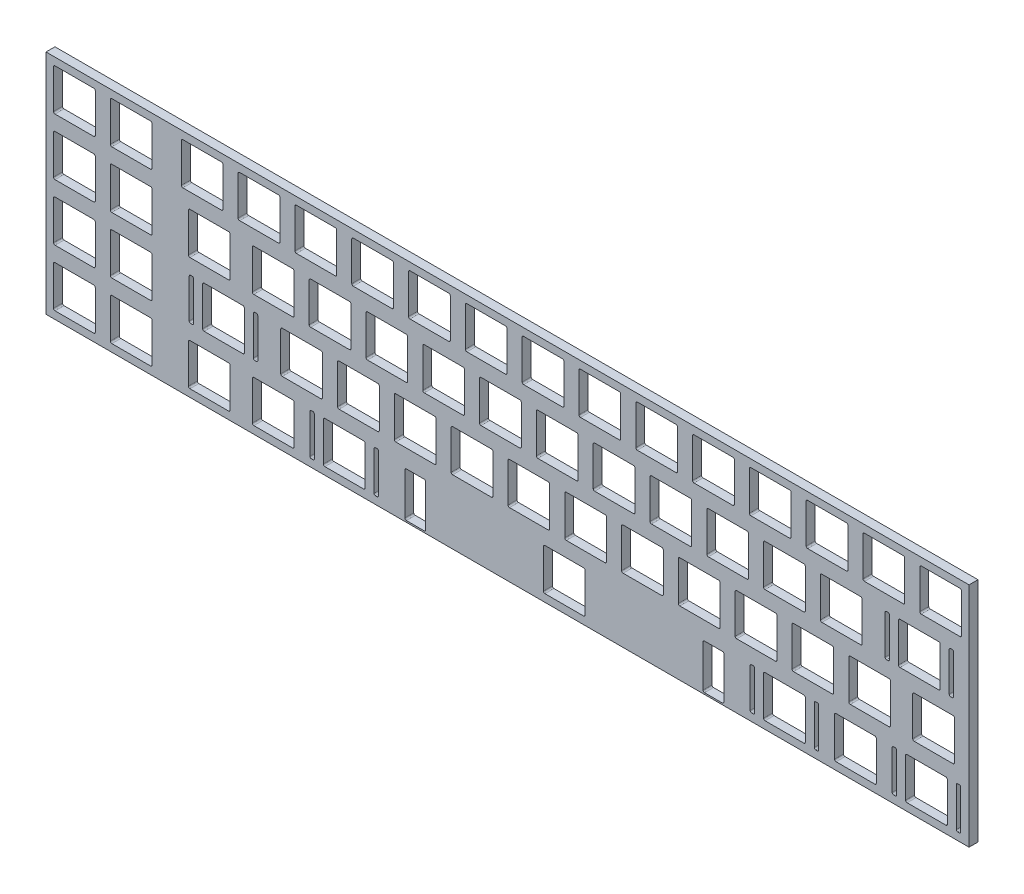
SolidWorks part; units mm, degrees
ref_plane "Front Plane" through (0, 0, 0) normal (0, 0, 1) x (1, 0, 0)
ref_plane "Top Plane" through (0, 0, 0) normal (0, 1, 0) x (1, 0, 0)
ref_plane "Right Plane" through (0, 0, 0) normal (1, 0, 0) x (0, 0, -1)
sketch "Model" plane through (0, 0, 0) normal (0, 0, 1) x (1, 0, 0)
  line L0 (3.025, -2.525) -> (16.025, -2.525)
  line L1 (3.025, -16.525) -> (16.025, -16.525)
  line L2 (2.525, -3.025) -> (2.525, -16.025)
  line L3 (16.525, -3.025) -> (16.525, -16.025)
  line L4 (22.075, -2.525) -> (35.075, -2.525)
  line L5 (22.075, -16.525) -> (35.075, -16.525)
  line L6 (21.575, -3.025) -> (21.575, -16.025)
  line L7 (35.575, -3.025) -> (35.575, -16.025)
  line L8 (45.8875, -2.525) -> (58.8875, -2.525)
  line L9 (45.8875, -16.525) -> (58.8875, -16.525)
  line L10 (45.3875, -3.025) -> (45.3875, -16.025)
  line L11 (59.3875, -3.025) -> (59.3875, -16.025)
  line L12 (64.9375, -2.525) -> (77.9375, -2.525)
  line L13 (64.9375, -16.525) -> (77.9375, -16.525)
  line L14 (64.4375, -3.025) -> (64.4375, -16.025)
  line L15 (78.4375, -3.025) -> (78.4375, -16.025)
  line L16 (83.9875, -2.525) -> (96.9875, -2.525)
  line L17 (83.9875, -16.525) -> (96.9875, -16.525)
  line L18 (83.4875, -3.025) -> (83.4875, -16.025)
  line L19 (97.4875, -3.025) -> (97.4875, -16.025)
  line L20 (103.0375, -2.525) -> (116.0375, -2.525)
  line L21 (103.0375, -16.525) -> (116.0375, -16.525)
  line L22 (102.5375, -3.025) -> (102.5375, -16.025)
  line L23 (116.5375, -3.025) -> (116.5375, -16.025)
  line L24 (122.0875, -2.525) -> (135.0875, -2.525)
  line L25 (122.0875, -16.525) -> (135.0875, -16.525)
  line L26 (121.5875, -3.025) -> (121.5875, -16.025)
  line L27 (135.5875, -3.025) -> (135.5875, -16.025)
  line L28 (141.1375, -2.525) -> (154.1375, -2.525)
  line L29 (141.1375, -16.525) -> (154.1375, -16.525)
  line L30 (140.6375, -3.025) -> (140.6375, -16.025)
  line L31 (154.6375, -3.025) -> (154.6375, -16.025)
  line L32 (160.1875, -2.525) -> (173.1875, -2.525)
  line L33 (160.1875, -16.525) -> (173.1875, -16.525)
  line L34 (159.6875, -3.025) -> (159.6875, -16.025)
  line L35 (173.6875, -3.025) -> (173.6875, -16.025)
  line L36 (179.2375, -2.525) -> (192.2375, -2.525)
  line L37 (179.2375, -16.525) -> (192.2375, -16.525)
  line L38 (178.7375, -3.025) -> (178.7375, -16.025)
  line L39 (192.7375, -3.025) -> (192.7375, -16.025)
  line L40 (198.2875, -2.525) -> (211.2875, -2.525)
  line L41 (198.2875, -16.525) -> (211.2875, -16.525)
  line L42 (197.7875, -3.025) -> (197.7875, -16.025)
  line L43 (211.7875, -3.025) -> (211.7875, -16.025)
  line L44 (217.3375, -2.525) -> (230.3375, -2.525)
  line L45 (217.3375, -16.525) -> (230.3375, -16.525)
  line L46 (216.8375, -3.025) -> (216.8375, -16.025)
  line L47 (230.8375, -3.025) -> (230.8375, -16.025)
  line L48 (236.3875, -2.525) -> (249.3875, -2.525)
  line L49 (236.3875, -16.525) -> (249.3875, -16.525)
  line L50 (235.8875, -3.025) -> (235.8875, -16.025)
  line L51 (249.8875, -3.025) -> (249.8875, -16.025)
  line L52 (255.4375, -2.525) -> (268.4375, -2.525)
  line L53 (255.4375, -16.525) -> (268.4375, -16.525)
  line L54 (254.9375, -3.025) -> (254.9375, -16.025)
  line L55 (268.9375, -3.025) -> (268.9375, -16.025)
  line L56 (274.4875, -2.525) -> (287.4875, -2.525)
  line L57 (274.4875, -16.525) -> (287.4875, -16.525)
  line L58 (273.9875, -3.025) -> (273.9875, -16.025)
  line L59 (287.9875, -3.025) -> (287.9875, -16.025)
  line L60 (293.5375, -2.525) -> (306.5375, -2.525)
  line L61 (293.5375, -16.525) -> (306.5375, -16.525)
  line L62 (293.0375, -3.025) -> (293.0375, -16.025)
  line L63 (307.0375, -3.025) -> (307.0375, -16.025)
  line L64 (3.025, -21.575) -> (16.025, -21.575)
  line L65 (3.025, -35.575) -> (16.025, -35.575)
  line L66 (2.525, -22.075) -> (2.525, -35.075)
  line L67 (16.525, -22.075) -> (16.525, -35.075)
  line L68 (22.075, -21.575) -> (35.075, -21.575)
  line L69 (22.075, -35.575) -> (35.075, -35.575)
  line L70 (21.575, -22.075) -> (21.575, -35.075)
  line L71 (35.575, -22.075) -> (35.575, -35.075)
  line L72 (48.2687, -21.575) -> (61.2687, -21.575)
  line L73 (48.2687, -35.575) -> (61.2687, -35.575)
  line L74 (47.7687, -22.075) -> (47.7687, -35.075)
  line L75 (61.7687, -22.075) -> (61.7687, -35.075)
  line L76 (69.7, -21.575) -> (82.7, -21.575)
  line L77 (69.7, -35.575) -> (82.7, -35.575)
  line L78 (69.2, -22.075) -> (69.2, -35.075)
  line L79 (83.2, -22.075) -> (83.2, -35.075)
  line L80 (88.75, -21.575) -> (101.75, -21.575)
  line L81 (88.75, -35.575) -> (101.75, -35.575)
  line L82 (88.25, -22.075) -> (88.25, -35.075)
  line L83 (102.25, -22.075) -> (102.25, -35.075)
  line L84 (107.8, -21.575) -> (120.8, -21.575)
  line L85 (107.8, -35.575) -> (120.8, -35.575)
  line L86 (107.3, -22.075) -> (107.3, -35.075)
  line L87 (121.3, -22.075) -> (121.3, -35.075)
  line L88 (126.85, -21.575) -> (139.85, -21.575)
  line L89 (126.85, -35.575) -> (139.85, -35.575)
  line L90 (126.35, -22.075) -> (126.35, -35.075)
  line L91 (140.35, -22.075) -> (140.35, -35.075)
  line L92 (145.9, -21.575) -> (158.9, -21.575)
  line L93 (145.9, -35.575) -> (158.9, -35.575)
  line L94 (145.4, -22.075) -> (145.4, -35.075)
  line L95 (159.4, -22.075) -> (159.4, -35.075)
  line L96 (164.95, -21.575) -> (177.95, -21.575)
  line L97 (164.95, -35.575) -> (177.95, -35.575)
  line L98 (164.45, -22.075) -> (164.45, -35.075)
  line L99 (178.45, -22.075) -> (178.45, -35.075)
  line L100 (184, -21.575) -> (197, -21.575)
  line L101 (184, -35.575) -> (197, -35.575)
  line L102 (183.5, -22.075) -> (183.5, -35.075)
  line L103 (197.5, -22.075) -> (197.5, -35.075)
  line L104 (203.05, -21.575) -> (216.05, -21.575)
  line L105 (203.05, -35.575) -> (216.05, -35.575)
  line L106 (202.55, -22.075) -> (202.55, -35.075)
  line L107 (216.55, -22.075) -> (216.55, -35.075)
  line L108 (222.1, -21.575) -> (235.1, -21.575)
  line L109 (222.1, -35.575) -> (235.1, -35.575)
  line L110 (221.6, -22.075) -> (221.6, -35.075)
  line L111 (235.6, -22.075) -> (235.6, -35.075)
  line L112 (241.15, -21.575) -> (254.15, -21.575)
  line L113 (241.15, -35.575) -> (254.15, -35.575)
  line L114 (240.65, -22.075) -> (240.65, -35.075)
  line L115 (254.65, -22.075) -> (254.65, -35.075)
  line L116 (260.2, -21.575) -> (273.2, -21.575)
  line L117 (260.2, -35.575) -> (273.2, -35.575)
  line L118 (259.7, -22.075) -> (259.7, -35.075)
  line L119 (273.7, -22.075) -> (273.7, -35.075)
  line L120 (286.3938, -21.575) -> (299.3938, -21.575)
  line L121 (286.3938, -35.575) -> (299.3938, -35.575)
  line L122 (285.8938, -22.075) -> (285.8938, -35.075)
  line L123 (299.8938, -22.075) -> (299.8938, -35.075)
  line L124 (281.8938, -21.575) -> (282.3938, -21.575)
  line L125 (281.8938, -35.575) -> (282.3938, -35.575)
  line L126 (281.3938, -22.075) -> (281.3938, -35.075)
  line L127 (282.8938, -22.075) -> (282.8938, -35.075)
  line L128 (303.3938, -21.575) -> (303.8938, -21.575)
  line L129 (303.3938, -35.575) -> (303.8938, -35.575)
  line L130 (302.8938, -22.075) -> (302.8938, -35.075)
  line L131 (304.3938, -22.075) -> (304.3938, -35.075)
  line L132 (3.025, -40.625) -> (16.025, -40.625)
  line L133 (3.025, -54.625) -> (16.025, -54.625)
  line L134 (2.525, -41.125) -> (2.525, -54.125)
  line L135 (16.525, -41.125) -> (16.525, -54.125)
  line L136 (22.075, -40.625) -> (35.075, -40.625)
  line L137 (22.075, -54.625) -> (35.075, -54.625)
  line L138 (21.575, -41.125) -> (21.575, -54.125)
  line L139 (35.575, -41.125) -> (35.575, -54.125)
  line L140 (53.0312, -40.625) -> (66.0312, -40.625)
  line L141 (53.0312, -54.625) -> (66.0312, -54.625)
  line L142 (52.5312, -41.125) -> (52.5312, -54.125)
  line L143 (66.5312, -41.125) -> (66.5312, -54.125)
  line L144 (48.5312, -40.625) -> (49.0312, -40.625)
  line L145 (48.5312, -54.625) -> (49.0312, -54.625)
  line L146 (48.0312, -41.125) -> (48.0312, -54.125)
  line L147 (49.5312, -41.125) -> (49.5312, -54.125)
  line L148 (70.0312, -40.625) -> (70.5312, -40.625)
  line L149 (70.0312, -54.625) -> (70.5312, -54.625)
  line L150 (69.5312, -41.125) -> (69.5312, -54.125)
  line L151 (71.0312, -41.125) -> (71.0312, -54.125)
  line L152 (79.225, -40.625) -> (92.225, -40.625)
  line L153 (79.225, -54.625) -> (92.225, -54.625)
  line L154 (78.725, -41.125) -> (78.725, -54.125)
  line L155 (92.725, -41.125) -> (92.725, -54.125)
  line L156 (98.275, -40.625) -> (111.275, -40.625)
  line L157 (98.275, -54.625) -> (111.275, -54.625)
  line L158 (97.775, -41.125) -> (97.775, -54.125)
  line L159 (111.775, -41.125) -> (111.775, -54.125)
  line L160 (117.325, -40.625) -> (130.325, -40.625)
  line L161 (117.325, -54.625) -> (130.325, -54.625)
  line L162 (116.825, -41.125) -> (116.825, -54.125)
  line L163 (130.825, -41.125) -> (130.825, -54.125)
  line L164 (136.375, -40.625) -> (149.375, -40.625)
  line L165 (136.375, -54.625) -> (149.375, -54.625)
  line L166 (135.875, -41.125) -> (135.875, -54.125)
  line L167 (149.875, -41.125) -> (149.875, -54.125)
  line L168 (155.425, -40.625) -> (168.425, -40.625)
  line L169 (155.425, -54.625) -> (168.425, -54.625)
  line L170 (154.925, -41.125) -> (154.925, -54.125)
  line L171 (168.925, -41.125) -> (168.925, -54.125)
  line L172 (174.475, -40.625) -> (187.475, -40.625)
  line L173 (174.475, -54.625) -> (187.475, -54.625)
  line L174 (173.975, -41.125) -> (173.975, -54.125)
  line L175 (187.975, -41.125) -> (187.975, -54.125)
  line L176 (193.525, -40.625) -> (206.525, -40.625)
  line L177 (193.525, -54.625) -> (206.525, -54.625)
  line L178 (193.025, -41.125) -> (193.025, -54.125)
  line L179 (207.025, -41.125) -> (207.025, -54.125)
  line L180 (212.575, -40.625) -> (225.575, -40.625)
  line L181 (212.575, -54.625) -> (225.575, -54.625)
  line L182 (212.075, -41.125) -> (212.075, -54.125)
  line L183 (226.075, -41.125) -> (226.075, -54.125)
  line L184 (231.625, -40.625) -> (244.625, -40.625)
  line L185 (231.625, -54.625) -> (244.625, -54.625)
  line L186 (231.125, -41.125) -> (231.125, -54.125)
  line L187 (245.125, -41.125) -> (245.125, -54.125)
  line L188 (250.675, -40.625) -> (263.675, -40.625)
  line L189 (250.675, -54.625) -> (263.675, -54.625)
  line L190 (250.175, -41.125) -> (250.175, -54.125)
  line L191 (264.175, -41.125) -> (264.175, -54.125)
  line L192 (269.725, -40.625) -> (282.725, -40.625)
  line L193 (269.725, -54.625) -> (282.725, -54.625)
  line L194 (269.225, -41.125) -> (269.225, -54.125)
  line L195 (283.225, -41.125) -> (283.225, -54.125)
  line L196 (291.1562, -40.625) -> (304.1562, -40.625)
  line L197 (291.1562, -54.625) -> (304.1562, -54.625)
  line L198 (290.6562, -41.125) -> (290.6562, -54.125)
  line L199 (304.6562, -41.125) -> (304.6562, -54.125)
  line L200 (3.025, -59.675) -> (16.025, -59.675)
  line L201 (3.025, -73.675) -> (16.025, -73.675)
  line L202 (2.525, -60.175) -> (2.525, -73.175)
  line L203 (16.525, -60.175) -> (16.525, -73.175)
  line L204 (22.075, -59.675) -> (35.075, -59.675)
  line L205 (22.075, -73.675) -> (35.075, -73.675)
  line L206 (21.575, -60.175) -> (21.575, -73.175)
  line L207 (35.575, -60.175) -> (35.575, -73.175)
  line L208 (48.2687, -59.675) -> (61.2687, -59.675)
  line L209 (48.2687, -73.675) -> (61.2687, -73.675)
  line L210 (47.7687, -60.175) -> (47.7687, -73.175)
  line L211 (61.7687, -60.175) -> (61.7687, -73.175)
  line L212 (69.7, -59.675) -> (82.7, -59.675)
  line L213 (69.7, -73.675) -> (82.7, -73.675)
  line L214 (69.2, -60.175) -> (69.2, -73.175)
  line L215 (83.2, -60.175) -> (83.2, -73.175)
  line L216 (93.5125, -59.675) -> (106.5125, -59.675)
  line L217 (93.5125, -73.675) -> (106.5125, -73.675)
  line L218 (93.0125, -60.175) -> (93.0125, -73.175)
  line L219 (107.0125, -60.175) -> (107.0125, -73.175)
  line L220 (89.0125, -59.675) -> (89.5125, -59.675)
  line L221 (89.0125, -73.675) -> (89.5125, -73.675)
  line L222 (88.5125, -60.175) -> (88.5125, -73.175)
  line L223 (90.0125, -60.175) -> (90.0125, -73.175)
  line L224 (110.5125, -59.675) -> (111.0125, -59.675)
  line L225 (110.5125, -73.675) -> (111.0125, -73.675)
  line L226 (110.0125, -60.175) -> (110.0125, -73.175)
  line L227 (111.5125, -60.175) -> (111.5125, -73.175)
  line L228 (167.3313, -59.675) -> (180.3313, -59.675)
  line L229 (167.3313, -73.675) -> (180.3313, -73.675)
  line L230 (166.8313, -60.175) -> (166.8313, -73.175)
  line L231 (180.8313, -60.175) -> (180.8313, -73.175)
  line L232 (120.8312, -60.675) -> (126.8313, -60.675)
  line L233 (120.8312, -75.675) -> (126.8313, -75.675)
  line L234 (120.3312, -61.175) -> (120.3312, -75.175)
  line L235 (127.3313, -61.175) -> (127.3313, -75.175)
  line L236 (220.8313, -60.675) -> (226.8313, -60.675)
  line L237 (220.8313, -75.675) -> (226.8313, -75.675)
  line L238 (220.3313, -61.175) -> (220.3313, -75.175)
  line L239 (227.3313, -61.175) -> (227.3313, -75.175)
  line L240 (241.15, -59.675) -> (254.15, -59.675)
  line L241 (241.15, -73.675) -> (254.15, -73.675)
  line L242 (240.65, -60.175) -> (240.65, -73.175)
  line L243 (254.65, -60.175) -> (254.65, -73.175)
  line L244 (236.65, -59.675) -> (237.15, -59.675)
  line L245 (236.65, -73.675) -> (237.15, -73.675)
  line L246 (236.15, -60.175) -> (236.15, -73.175)
  line L247 (237.65, -60.175) -> (237.65, -73.175)
  line L248 (258.15, -59.675) -> (258.65, -59.675)
  line L249 (258.15, -73.675) -> (258.65, -73.675)
  line L250 (257.65, -60.175) -> (257.65, -73.175)
  line L251 (259.15, -60.175) -> (259.15, -73.175)
  line L252 (264.9625, -59.675) -> (277.9625, -59.675)
  line L253 (264.9625, -73.675) -> (277.9625, -73.675)
  line L254 (264.4625, -60.175) -> (264.4625, -73.175)
  line L255 (278.4625, -60.175) -> (278.4625, -73.175)
  line L256 (288.775, -59.675) -> (301.775, -59.675)
  line L257 (288.775, -73.675) -> (301.775, -73.675)
  line L258 (288.275, -60.175) -> (288.275, -73.175)
  line L259 (302.275, -60.175) -> (302.275, -73.175)
  line L260 (284.275, -59.675) -> (284.775, -59.675)
  line L261 (284.275, -73.675) -> (284.775, -73.675)
  line L262 (283.775, -60.175) -> (283.775, -73.175)
  line L263 (285.275, -60.175) -> (285.275, -73.175)
  line L264 (305.775, -59.675) -> (306.275, -59.675)
  line L265 (305.775, -73.675) -> (306.275, -73.675)
  line L266 (305.275, -60.175) -> (305.275, -73.175)
  line L267 (306.775, -60.175) -> (306.775, -73.175)
  line L268 (0, -76.2) -> (309.5625, -76.2)
  line L269 (0, 0) -> (309.5625, 0)
  line L270 (0, -76.2) -> (0, 0)
  line L271 (309.5625, -76.2) -> (309.5625, 0)
  arc A0 (3.025, -2.525) -> (2.525, -3.025) centre (3.025, -3.025) ccw
  arc A1 (16.525, -3.025) -> (16.025, -2.525) centre (16.025, -3.025) ccw
  arc A2 (2.525, -16.025) -> (3.025, -16.525) centre (3.025, -16.025) ccw
  arc A3 (16.025, -16.525) -> (16.525, -16.025) centre (16.025, -16.025) ccw
  arc A4 (22.075, -2.525) -> (21.575, -3.025) centre (22.075, -3.025) ccw
  arc A5 (35.575, -3.025) -> (35.075, -2.525) centre (35.075, -3.025) ccw
  arc A6 (21.575, -16.025) -> (22.075, -16.525) centre (22.075, -16.025) ccw
  arc A7 (35.075, -16.525) -> (35.575, -16.025) centre (35.075, -16.025) ccw
  arc A8 (45.8875, -2.525) -> (45.3875, -3.025) centre (45.8875, -3.025) ccw
  arc A9 (59.3875, -3.025) -> (58.8875, -2.525) centre (58.8875, -3.025) ccw
  arc A10 (45.3875, -16.025) -> (45.8875, -16.525) centre (45.8875, -16.025) ccw
  arc A11 (58.8875, -16.525) -> (59.3875, -16.025) centre (58.8875, -16.025) ccw
  arc A12 (64.9375, -2.525) -> (64.4375, -3.025) centre (64.9375, -3.025) ccw
  arc A13 (78.4375, -3.025) -> (77.9375, -2.525) centre (77.9375, -3.025) ccw
  arc A14 (64.4375, -16.025) -> (64.9375, -16.525) centre (64.9375, -16.025) ccw
  arc A15 (77.9375, -16.525) -> (78.4375, -16.025) centre (77.9375, -16.025) ccw
  arc A16 (83.9875, -2.525) -> (83.4875, -3.025) centre (83.9875, -3.025) ccw
  arc A17 (97.4875, -3.025) -> (96.9875, -2.525) centre (96.9875, -3.025) ccw
  arc A18 (83.4875, -16.025) -> (83.9875, -16.525) centre (83.9875, -16.025) ccw
  arc A19 (96.9875, -16.525) -> (97.4875, -16.025) centre (96.9875, -16.025) ccw
  arc A20 (103.0375, -2.525) -> (102.5375, -3.025) centre (103.0375, -3.025) ccw
  arc A21 (116.5375, -3.025) -> (116.0375, -2.525) centre (116.0375, -3.025) ccw
  arc A22 (102.5375, -16.025) -> (103.0375, -16.525) centre (103.0375, -16.025) ccw
  arc A23 (116.0375, -16.525) -> (116.5375, -16.025) centre (116.0375, -16.025) ccw
  arc A24 (122.0875, -2.525) -> (121.5875, -3.025) centre (122.0875, -3.025) ccw
  arc A25 (135.5875, -3.025) -> (135.0875, -2.525) centre (135.0875, -3.025) ccw
  arc A26 (121.5875, -16.025) -> (122.0875, -16.525) centre (122.0875, -16.025) ccw
  arc A27 (135.0875, -16.525) -> (135.5875, -16.025) centre (135.0875, -16.025) ccw
  arc A28 (141.1375, -2.525) -> (140.6375, -3.025) centre (141.1375, -3.025) ccw
  arc A29 (154.6375, -3.025) -> (154.1375, -2.525) centre (154.1375, -3.025) ccw
  arc A30 (140.6375, -16.025) -> (141.1375, -16.525) centre (141.1375, -16.025) ccw
  arc A31 (154.1375, -16.525) -> (154.6375, -16.025) centre (154.1375, -16.025) ccw
  arc A32 (160.1875, -2.525) -> (159.6875, -3.025) centre (160.1875, -3.025) ccw
  arc A33 (173.6875, -3.025) -> (173.1875, -2.525) centre (173.1875, -3.025) ccw
  arc A34 (159.6875, -16.025) -> (160.1875, -16.525) centre (160.1875, -16.025) ccw
  arc A35 (173.1875, -16.525) -> (173.6875, -16.025) centre (173.1875, -16.025) ccw
  arc A36 (179.2375, -2.525) -> (178.7375, -3.025) centre (179.2375, -3.025) ccw
  arc A37 (192.7375, -3.025) -> (192.2375, -2.525) centre (192.2375, -3.025) ccw
  arc A38 (178.7375, -16.025) -> (179.2375, -16.525) centre (179.2375, -16.025) ccw
  arc A39 (192.2375, -16.525) -> (192.7375, -16.025) centre (192.2375, -16.025) ccw
  arc A40 (198.2875, -2.525) -> (197.7875, -3.025) centre (198.2875, -3.025) ccw
  arc A41 (211.7875, -3.025) -> (211.2875, -2.525) centre (211.2875, -3.025) ccw
  arc A42 (197.7875, -16.025) -> (198.2875, -16.525) centre (198.2875, -16.025) ccw
  arc A43 (211.2875, -16.525) -> (211.7875, -16.025) centre (211.2875, -16.025) ccw
  arc A44 (217.3375, -2.525) -> (216.8375, -3.025) centre (217.3375, -3.025) ccw
  arc A45 (230.8375, -3.025) -> (230.3375, -2.525) centre (230.3375, -3.025) ccw
  arc A46 (216.8375, -16.025) -> (217.3375, -16.525) centre (217.3375, -16.025) ccw
  arc A47 (230.3375, -16.525) -> (230.8375, -16.025) centre (230.3375, -16.025) ccw
  arc A48 (236.3875, -2.525) -> (235.8875, -3.025) centre (236.3875, -3.025) ccw
  arc A49 (249.8875, -3.025) -> (249.3875, -2.525) centre (249.3875, -3.025) ccw
  arc A50 (235.8875, -16.025) -> (236.3875, -16.525) centre (236.3875, -16.025) ccw
  arc A51 (249.3875, -16.525) -> (249.8875, -16.025) centre (249.3875, -16.025) ccw
  arc A52 (255.4375, -2.525) -> (254.9375, -3.025) centre (255.4375, -3.025) ccw
  arc A53 (268.9375, -3.025) -> (268.4375, -2.525) centre (268.4375, -3.025) ccw
  arc A54 (254.9375, -16.025) -> (255.4375, -16.525) centre (255.4375, -16.025) ccw
  arc A55 (268.4375, -16.525) -> (268.9375, -16.025) centre (268.4375, -16.025) ccw
  arc A56 (274.4875, -2.525) -> (273.9875, -3.025) centre (274.4875, -3.025) ccw
  arc A57 (287.9875, -3.025) -> (287.4875, -2.525) centre (287.4875, -3.025) ccw
  arc A58 (273.9875, -16.025) -> (274.4875, -16.525) centre (274.4875, -16.025) ccw
  arc A59 (287.4875, -16.525) -> (287.9875, -16.025) centre (287.4875, -16.025) ccw
  arc A60 (293.5375, -2.525) -> (293.0375, -3.025) centre (293.5375, -3.025) ccw
  arc A61 (307.0375, -3.025) -> (306.5375, -2.525) centre (306.5375, -3.025) ccw
  arc A62 (293.0375, -16.025) -> (293.5375, -16.525) centre (293.5375, -16.025) ccw
  arc A63 (306.5375, -16.525) -> (307.0375, -16.025) centre (306.5375, -16.025) ccw
  arc A64 (3.025, -21.575) -> (2.525, -22.075) centre (3.025, -22.075) ccw
  arc A65 (16.525, -22.075) -> (16.025, -21.575) centre (16.025, -22.075) ccw
  arc A66 (2.525, -35.075) -> (3.025, -35.575) centre (3.025, -35.075) ccw
  arc A67 (16.025, -35.575) -> (16.525, -35.075) centre (16.025, -35.075) ccw
  arc A68 (22.075, -21.575) -> (21.575, -22.075) centre (22.075, -22.075) ccw
  arc A69 (35.575, -22.075) -> (35.075, -21.575) centre (35.075, -22.075) ccw
  arc A70 (21.575, -35.075) -> (22.075, -35.575) centre (22.075, -35.075) ccw
  arc A71 (35.075, -35.575) -> (35.575, -35.075) centre (35.075, -35.075) ccw
  arc A72 (48.2687, -21.575) -> (47.7687, -22.075) centre (48.2687, -22.075) ccw
  arc A73 (61.7687, -22.075) -> (61.2687, -21.575) centre (61.2687, -22.075) ccw
  arc A74 (47.7687, -35.075) -> (48.2687, -35.575) centre (48.2687, -35.075) ccw
  arc A75 (61.2687, -35.575) -> (61.7687, -35.075) centre (61.2687, -35.075) ccw
  arc A76 (69.7, -21.575) -> (69.2, -22.075) centre (69.7, -22.075) ccw
  arc A77 (83.2, -22.075) -> (82.7, -21.575) centre (82.7, -22.075) ccw
  arc A78 (69.2, -35.075) -> (69.7, -35.575) centre (69.7, -35.075) ccw
  arc A79 (82.7, -35.575) -> (83.2, -35.075) centre (82.7, -35.075) ccw
  arc A80 (88.75, -21.575) -> (88.25, -22.075) centre (88.75, -22.075) ccw
  arc A81 (102.25, -22.075) -> (101.75, -21.575) centre (101.75, -22.075) ccw
  arc A82 (88.25, -35.075) -> (88.75, -35.575) centre (88.75, -35.075) ccw
  arc A83 (101.75, -35.575) -> (102.25, -35.075) centre (101.75, -35.075) ccw
  arc A84 (107.8, -21.575) -> (107.3, -22.075) centre (107.8, -22.075) ccw
  arc A85 (121.3, -22.075) -> (120.8, -21.575) centre (120.8, -22.075) ccw
  arc A86 (107.3, -35.075) -> (107.8, -35.575) centre (107.8, -35.075) ccw
  arc A87 (120.8, -35.575) -> (121.3, -35.075) centre (120.8, -35.075) ccw
  arc A88 (126.85, -21.575) -> (126.35, -22.075) centre (126.85, -22.075) ccw
  arc A89 (140.35, -22.075) -> (139.85, -21.575) centre (139.85, -22.075) ccw
  arc A90 (126.35, -35.075) -> (126.85, -35.575) centre (126.85, -35.075) ccw
  arc A91 (139.85, -35.575) -> (140.35, -35.075) centre (139.85, -35.075) ccw
  arc A92 (145.9, -21.575) -> (145.4, -22.075) centre (145.9, -22.075) ccw
  arc A93 (159.4, -22.075) -> (158.9, -21.575) centre (158.9, -22.075) ccw
  arc A94 (145.4, -35.075) -> (145.9, -35.575) centre (145.9, -35.075) ccw
  arc A95 (158.9, -35.575) -> (159.4, -35.075) centre (158.9, -35.075) ccw
  arc A96 (164.95, -21.575) -> (164.45, -22.075) centre (164.95, -22.075) ccw
  arc A97 (178.45, -22.075) -> (177.95, -21.575) centre (177.95, -22.075) ccw
  arc A98 (164.45, -35.075) -> (164.95, -35.575) centre (164.95, -35.075) ccw
  arc A99 (177.95, -35.575) -> (178.45, -35.075) centre (177.95, -35.075) ccw
  arc A100 (184, -21.575) -> (183.5, -22.075) centre (184, -22.075) ccw
  arc A101 (197.5, -22.075) -> (197, -21.575) centre (197, -22.075) ccw
  arc A102 (183.5, -35.075) -> (184, -35.575) centre (184, -35.075) ccw
  arc A103 (197, -35.575) -> (197.5, -35.075) centre (197, -35.075) ccw
  arc A104 (203.05, -21.575) -> (202.55, -22.075) centre (203.05, -22.075) ccw
  arc A105 (216.55, -22.075) -> (216.05, -21.575) centre (216.05, -22.075) ccw
  arc A106 (202.55, -35.075) -> (203.05, -35.575) centre (203.05, -35.075) ccw
  arc A107 (216.05, -35.575) -> (216.55, -35.075) centre (216.05, -35.075) ccw
  arc A108 (222.1, -21.575) -> (221.6, -22.075) centre (222.1, -22.075) ccw
  arc A109 (235.6, -22.075) -> (235.1, -21.575) centre (235.1, -22.075) ccw
  arc A110 (221.6, -35.075) -> (222.1, -35.575) centre (222.1, -35.075) ccw
  arc A111 (235.1, -35.575) -> (235.6, -35.075) centre (235.1, -35.075) ccw
  arc A112 (241.15, -21.575) -> (240.65, -22.075) centre (241.15, -22.075) ccw
  arc A113 (254.65, -22.075) -> (254.15, -21.575) centre (254.15, -22.075) ccw
  arc A114 (240.65, -35.075) -> (241.15, -35.575) centre (241.15, -35.075) ccw
  arc A115 (254.15, -35.575) -> (254.65, -35.075) centre (254.15, -35.075) ccw
  arc A116 (260.2, -21.575) -> (259.7, -22.075) centre (260.2, -22.075) ccw
  arc A117 (273.7, -22.075) -> (273.2, -21.575) centre (273.2, -22.075) ccw
  arc A118 (259.7, -35.075) -> (260.2, -35.575) centre (260.2, -35.075) ccw
  arc A119 (273.2, -35.575) -> (273.7, -35.075) centre (273.2, -35.075) ccw
  arc A120 (286.3938, -21.575) -> (285.8938, -22.075) centre (286.3938, -22.075) ccw
  arc A121 (299.8938, -22.075) -> (299.3938, -21.575) centre (299.3938, -22.075) ccw
  arc A122 (285.8938, -35.075) -> (286.3938, -35.575) centre (286.3938, -35.075) ccw
  arc A123 (299.3938, -35.575) -> (299.8938, -35.075) centre (299.3938, -35.075) ccw
  arc A124 (281.8938, -21.575) -> (281.3938, -22.075) centre (281.8938, -22.075) ccw
  arc A125 (282.8938, -22.075) -> (282.3938, -21.575) centre (282.3938, -22.075) ccw
  arc A126 (281.3938, -35.075) -> (281.8938, -35.575) centre (281.8938, -35.075) ccw
  arc A127 (282.3938, -35.575) -> (282.8938, -35.075) centre (282.3938, -35.075) ccw
  arc A128 (303.3938, -21.575) -> (302.8938, -22.075) centre (303.3938, -22.075) ccw
  arc A129 (304.3938, -22.075) -> (303.8938, -21.575) centre (303.8938, -22.075) ccw
  arc A130 (302.8938, -35.075) -> (303.3938, -35.575) centre (303.3938, -35.075) ccw
  arc A131 (303.8938, -35.575) -> (304.3938, -35.075) centre (303.8938, -35.075) ccw
  arc A132 (3.025, -40.625) -> (2.525, -41.125) centre (3.025, -41.125) ccw
  arc A133 (16.525, -41.125) -> (16.025, -40.625) centre (16.025, -41.125) ccw
  arc A134 (2.525, -54.125) -> (3.025, -54.625) centre (3.025, -54.125) ccw
  arc A135 (16.025, -54.625) -> (16.525, -54.125) centre (16.025, -54.125) ccw
  arc A136 (22.075, -40.625) -> (21.575, -41.125) centre (22.075, -41.125) ccw
  arc A137 (35.575, -41.125) -> (35.075, -40.625) centre (35.075, -41.125) ccw
  arc A138 (21.575, -54.125) -> (22.075, -54.625) centre (22.075, -54.125) ccw
  arc A139 (35.075, -54.625) -> (35.575, -54.125) centre (35.075, -54.125) ccw
  arc A140 (53.0312, -40.625) -> (52.5312, -41.125) centre (53.0312, -41.125) ccw
  arc A141 (66.5312, -41.125) -> (66.0312, -40.625) centre (66.0312, -41.125) ccw
  arc A142 (52.5312, -54.125) -> (53.0312, -54.625) centre (53.0312, -54.125) ccw
  arc A143 (66.0312, -54.625) -> (66.5312, -54.125) centre (66.0312, -54.125) ccw
  arc A144 (48.5312, -40.625) -> (48.0312, -41.125) centre (48.5312, -41.125) ccw
  arc A145 (49.5312, -41.125) -> (49.0312, -40.625) centre (49.0312, -41.125) ccw
  arc A146 (48.0312, -54.125) -> (48.5312, -54.625) centre (48.5312, -54.125) ccw
  arc A147 (49.0312, -54.625) -> (49.5312, -54.125) centre (49.0312, -54.125) ccw
  arc A148 (70.0312, -40.625) -> (69.5312, -41.125) centre (70.0312, -41.125) ccw
  arc A149 (71.0312, -41.125) -> (70.5312, -40.625) centre (70.5312, -41.125) ccw
  arc A150 (69.5312, -54.125) -> (70.0312, -54.625) centre (70.0312, -54.125) ccw
  arc A151 (70.5312, -54.625) -> (71.0312, -54.125) centre (70.5312, -54.125) ccw
  arc A152 (79.225, -40.625) -> (78.725, -41.125) centre (79.225, -41.125) ccw
  arc A153 (92.725, -41.125) -> (92.225, -40.625) centre (92.225, -41.125) ccw
  arc A154 (78.725, -54.125) -> (79.225, -54.625) centre (79.225, -54.125) ccw
  arc A155 (92.225, -54.625) -> (92.725, -54.125) centre (92.225, -54.125) ccw
  arc A156 (98.275, -40.625) -> (97.775, -41.125) centre (98.275, -41.125) ccw
  arc A157 (111.775, -41.125) -> (111.275, -40.625) centre (111.275, -41.125) ccw
  arc A158 (97.775, -54.125) -> (98.275, -54.625) centre (98.275, -54.125) ccw
  arc A159 (111.275, -54.625) -> (111.775, -54.125) centre (111.275, -54.125) ccw
  arc A160 (117.325, -40.625) -> (116.825, -41.125) centre (117.325, -41.125) ccw
  arc A161 (130.825, -41.125) -> (130.325, -40.625) centre (130.325, -41.125) ccw
  arc A162 (116.825, -54.125) -> (117.325, -54.625) centre (117.325, -54.125) ccw
  arc A163 (130.325, -54.625) -> (130.825, -54.125) centre (130.325, -54.125) ccw
  arc A164 (136.375, -40.625) -> (135.875, -41.125) centre (136.375, -41.125) ccw
  arc A165 (149.875, -41.125) -> (149.375, -40.625) centre (149.375, -41.125) ccw
  arc A166 (135.875, -54.125) -> (136.375, -54.625) centre (136.375, -54.125) ccw
  arc A167 (149.375, -54.625) -> (149.875, -54.125) centre (149.375, -54.125) ccw
  arc A168 (155.425, -40.625) -> (154.925, -41.125) centre (155.425, -41.125) ccw
  arc A169 (168.925, -41.125) -> (168.425, -40.625) centre (168.425, -41.125) ccw
  arc A170 (154.925, -54.125) -> (155.425, -54.625) centre (155.425, -54.125) ccw
  arc A171 (168.425, -54.625) -> (168.925, -54.125) centre (168.425, -54.125) ccw
  arc A172 (174.475, -40.625) -> (173.975, -41.125) centre (174.475, -41.125) ccw
  arc A173 (187.975, -41.125) -> (187.475, -40.625) centre (187.475, -41.125) ccw
  arc A174 (173.975, -54.125) -> (174.475, -54.625) centre (174.475, -54.125) ccw
  arc A175 (187.475, -54.625) -> (187.975, -54.125) centre (187.475, -54.125) ccw
  arc A176 (193.525, -40.625) -> (193.025, -41.125) centre (193.525, -41.125) ccw
  arc A177 (207.025, -41.125) -> (206.525, -40.625) centre (206.525, -41.125) ccw
  arc A178 (193.025, -54.125) -> (193.525, -54.625) centre (193.525, -54.125) ccw
  arc A179 (206.525, -54.625) -> (207.025, -54.125) centre (206.525, -54.125) ccw
  arc A180 (212.575, -40.625) -> (212.075, -41.125) centre (212.575, -41.125) ccw
  arc A181 (226.075, -41.125) -> (225.575, -40.625) centre (225.575, -41.125) ccw
  arc A182 (212.075, -54.125) -> (212.575, -54.625) centre (212.575, -54.125) ccw
  arc A183 (225.575, -54.625) -> (226.075, -54.125) centre (225.575, -54.125) ccw
  arc A184 (231.625, -40.625) -> (231.125, -41.125) centre (231.625, -41.125) ccw
  arc A185 (245.125, -41.125) -> (244.625, -40.625) centre (244.625, -41.125) ccw
  arc A186 (231.125, -54.125) -> (231.625, -54.625) centre (231.625, -54.125) ccw
  arc A187 (244.625, -54.625) -> (245.125, -54.125) centre (244.625, -54.125) ccw
  arc A188 (250.675, -40.625) -> (250.175, -41.125) centre (250.675, -41.125) ccw
  arc A189 (264.175, -41.125) -> (263.675, -40.625) centre (263.675, -41.125) ccw
  arc A190 (250.175, -54.125) -> (250.675, -54.625) centre (250.675, -54.125) ccw
  arc A191 (263.675, -54.625) -> (264.175, -54.125) centre (263.675, -54.125) ccw
  arc A192 (269.725, -40.625) -> (269.225, -41.125) centre (269.725, -41.125) ccw
  arc A193 (283.225, -41.125) -> (282.725, -40.625) centre (282.725, -41.125) ccw
  arc A194 (269.225, -54.125) -> (269.725, -54.625) centre (269.725, -54.125) ccw
  arc A195 (282.725, -54.625) -> (283.225, -54.125) centre (282.725, -54.125) ccw
  arc A196 (291.1562, -40.625) -> (290.6562, -41.125) centre (291.1562, -41.125) ccw
  arc A197 (304.6562, -41.125) -> (304.1562, -40.625) centre (304.1562, -41.125) ccw
  arc A198 (290.6562, -54.125) -> (291.1562, -54.625) centre (291.1562, -54.125) ccw
  arc A199 (304.1562, -54.625) -> (304.6562, -54.125) centre (304.1562, -54.125) ccw
  arc A200 (3.025, -59.675) -> (2.525, -60.175) centre (3.025, -60.175) ccw
  arc A201 (16.525, -60.175) -> (16.025, -59.675) centre (16.025, -60.175) ccw
  arc A202 (2.525, -73.175) -> (3.025, -73.675) centre (3.025, -73.175) ccw
  arc A203 (16.025, -73.675) -> (16.525, -73.175) centre (16.025, -73.175) ccw
  arc A204 (22.075, -59.675) -> (21.575, -60.175) centre (22.075, -60.175) ccw
  arc A205 (35.575, -60.175) -> (35.075, -59.675) centre (35.075, -60.175) ccw
  arc A206 (21.575, -73.175) -> (22.075, -73.675) centre (22.075, -73.175) ccw
  arc A207 (35.075, -73.675) -> (35.575, -73.175) centre (35.075, -73.175) ccw
  arc A208 (48.2687, -59.675) -> (47.7687, -60.175) centre (48.2687, -60.175) ccw
  arc A209 (61.7687, -60.175) -> (61.2687, -59.675) centre (61.2687, -60.175) ccw
  arc A210 (47.7687, -73.175) -> (48.2687, -73.675) centre (48.2687, -73.175) ccw
  arc A211 (61.2687, -73.675) -> (61.7687, -73.175) centre (61.2687, -73.175) ccw
  arc A212 (69.7, -59.675) -> (69.2, -60.175) centre (69.7, -60.175) ccw
  arc A213 (83.2, -60.175) -> (82.7, -59.675) centre (82.7, -60.175) ccw
  arc A214 (69.2, -73.175) -> (69.7, -73.675) centre (69.7, -73.175) ccw
  arc A215 (82.7, -73.675) -> (83.2, -73.175) centre (82.7, -73.175) ccw
  arc A216 (93.5125, -59.675) -> (93.0125, -60.175) centre (93.5125, -60.175) ccw
  arc A217 (107.0125, -60.175) -> (106.5125, -59.675) centre (106.5125, -60.175) ccw
  arc A218 (93.0125, -73.175) -> (93.5125, -73.675) centre (93.5125, -73.175) ccw
  arc A219 (106.5125, -73.675) -> (107.0125, -73.175) centre (106.5125, -73.175) ccw
  arc A220 (89.0125, -59.675) -> (88.5125, -60.175) centre (89.0125, -60.175) ccw
  arc A221 (90.0125, -60.175) -> (89.5125, -59.675) centre (89.5125, -60.175) ccw
  arc A222 (88.5125, -73.175) -> (89.0125, -73.675) centre (89.0125, -73.175) ccw
  arc A223 (89.5125, -73.675) -> (90.0125, -73.175) centre (89.5125, -73.175) ccw
  arc A224 (110.5125, -59.675) -> (110.0125, -60.175) centre (110.5125, -60.175) ccw
  arc A225 (111.5125, -60.175) -> (111.0125, -59.675) centre (111.0125, -60.175) ccw
  arc A226 (110.0125, -73.175) -> (110.5125, -73.675) centre (110.5125, -73.175) ccw
  arc A227 (111.0125, -73.675) -> (111.5125, -73.175) centre (111.0125, -73.175) ccw
  arc A228 (167.3313, -59.675) -> (166.8313, -60.175) centre (167.3313, -60.175) ccw
  arc A229 (180.8313, -60.175) -> (180.3313, -59.675) centre (180.3313, -60.175) ccw
  arc A230 (166.8313, -73.175) -> (167.3313, -73.675) centre (167.3313, -73.175) ccw
  arc A231 (180.3313, -73.675) -> (180.8313, -73.175) centre (180.3313, -73.175) ccw
  arc A232 (120.8312, -60.675) -> (120.3312, -61.175) centre (120.8312, -61.175) ccw
  arc A233 (127.3313, -61.175) -> (126.8313, -60.675) centre (126.8313, -61.175) ccw
  arc A234 (120.3312, -75.175) -> (120.8312, -75.675) centre (120.8312, -75.175) ccw
  arc A235 (126.8313, -75.675) -> (127.3313, -75.175) centre (126.8313, -75.175) ccw
  arc A236 (220.8313, -60.675) -> (220.3313, -61.175) centre (220.8313, -61.175) ccw
  arc A237 (227.3313, -61.175) -> (226.8313, -60.675) centre (226.8313, -61.175) ccw
  arc A238 (220.3313, -75.175) -> (220.8313, -75.675) centre (220.8313, -75.175) ccw
  arc A239 (226.8313, -75.675) -> (227.3313, -75.175) centre (226.8313, -75.175) ccw
  arc A240 (241.15, -59.675) -> (240.65, -60.175) centre (241.15, -60.175) ccw
  arc A241 (254.65, -60.175) -> (254.15, -59.675) centre (254.15, -60.175) ccw
  arc A242 (240.65, -73.175) -> (241.15, -73.675) centre (241.15, -73.175) ccw
  arc A243 (254.15, -73.675) -> (254.65, -73.175) centre (254.15, -73.175) ccw
  arc A244 (236.65, -59.675) -> (236.15, -60.175) centre (236.65, -60.175) ccw
  arc A245 (237.65, -60.175) -> (237.15, -59.675) centre (237.15, -60.175) ccw
  arc A246 (236.15, -73.175) -> (236.65, -73.675) centre (236.65, -73.175) ccw
  arc A247 (237.15, -73.675) -> (237.65, -73.175) centre (237.15, -73.175) ccw
  arc A248 (258.15, -59.675) -> (257.65, -60.175) centre (258.15, -60.175) ccw
  arc A249 (259.15, -60.175) -> (258.65, -59.675) centre (258.65, -60.175) ccw
  arc A250 (257.65, -73.175) -> (258.15, -73.675) centre (258.15, -73.175) ccw
  arc A251 (258.65, -73.675) -> (259.15, -73.175) centre (258.65, -73.175) ccw
  arc A252 (264.9625, -59.675) -> (264.4625, -60.175) centre (264.9625, -60.175) ccw
  arc A253 (278.4625, -60.175) -> (277.9625, -59.675) centre (277.9625, -60.175) ccw
  arc A254 (264.4625, -73.175) -> (264.9625, -73.675) centre (264.9625, -73.175) ccw
  arc A255 (277.9625, -73.675) -> (278.4625, -73.175) centre (277.9625, -73.175) ccw
  arc A256 (288.775, -59.675) -> (288.275, -60.175) centre (288.775, -60.175) ccw
  arc A257 (302.275, -60.175) -> (301.775, -59.675) centre (301.775, -60.175) ccw
  arc A258 (288.275, -73.175) -> (288.775, -73.675) centre (288.775, -73.175) ccw
  arc A259 (301.775, -73.675) -> (302.275, -73.175) centre (301.775, -73.175) ccw
  arc A260 (284.275, -59.675) -> (283.775, -60.175) centre (284.275, -60.175) ccw
  arc A261 (285.275, -60.175) -> (284.775, -59.675) centre (284.775, -60.175) ccw
  arc A262 (283.775, -73.175) -> (284.275, -73.675) centre (284.275, -73.175) ccw
  arc A263 (284.775, -73.675) -> (285.275, -73.175) centre (284.775, -73.175) ccw
  arc A264 (305.775, -59.675) -> (305.275, -60.175) centre (305.775, -60.175) ccw
  arc A265 (306.775, -60.175) -> (306.275, -59.675) centre (306.275, -60.175) ccw
  arc A266 (305.275, -73.175) -> (305.775, -73.675) centre (305.775, -73.175) ccw
  arc A267 (306.275, -73.675) -> (306.775, -73.175) centre (306.275, -73.175) ccw
extrude "Boss-Extrude1" add sketch "Model" along normal blind 3
